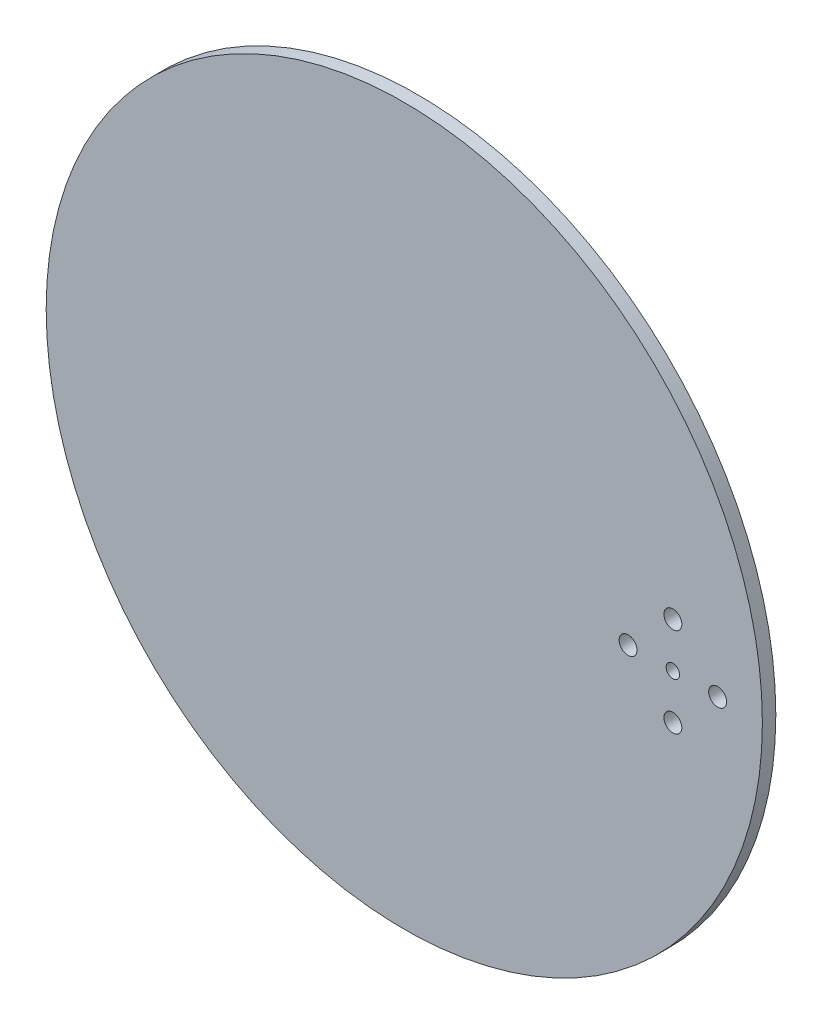
SolidWorks part; units mm, degrees
ref_plane "前视基准面" through (0, 0, 0) normal (0, 0, 1) x (1, 0, 0)
ref_plane "上视基准面" through (0, 0, 0) normal (0, 1, 0) x (1, 0, 0)
ref_plane "右视基准面" through (0, 0, 0) normal (1, 0, 0) x (0, 0, -1)
sketch "草图1" plane through (0, 0, 0) normal (0, 0, 1) x (1, 0, 0)
  circle A0 centre (0, 0) radius 80
  circle A1 centre (0, 0) radius 60 construction
extrude "凸台-拉伸1" add sketch "草图1" along normal blind 3
sketch "草图2" plane through (0, 0, 3) normal (0, 0, 1) x (1, 0, 0)
  circle A1 centre (60, 0) radius 15
  circle A2 centre (60, 0) radius 1.5
  circle A4 centre (70, 0) radius 2
  circle A5 centre (60, 10) radius 2
  circle A6 centre (50, 0) radius 2
  circle A7 centre (60, -10) radius 2
extrude "切除-拉伸4" cut sketch "草图2" against normal blind 3 contours A4 | A7 | A2 | A6 | A5
